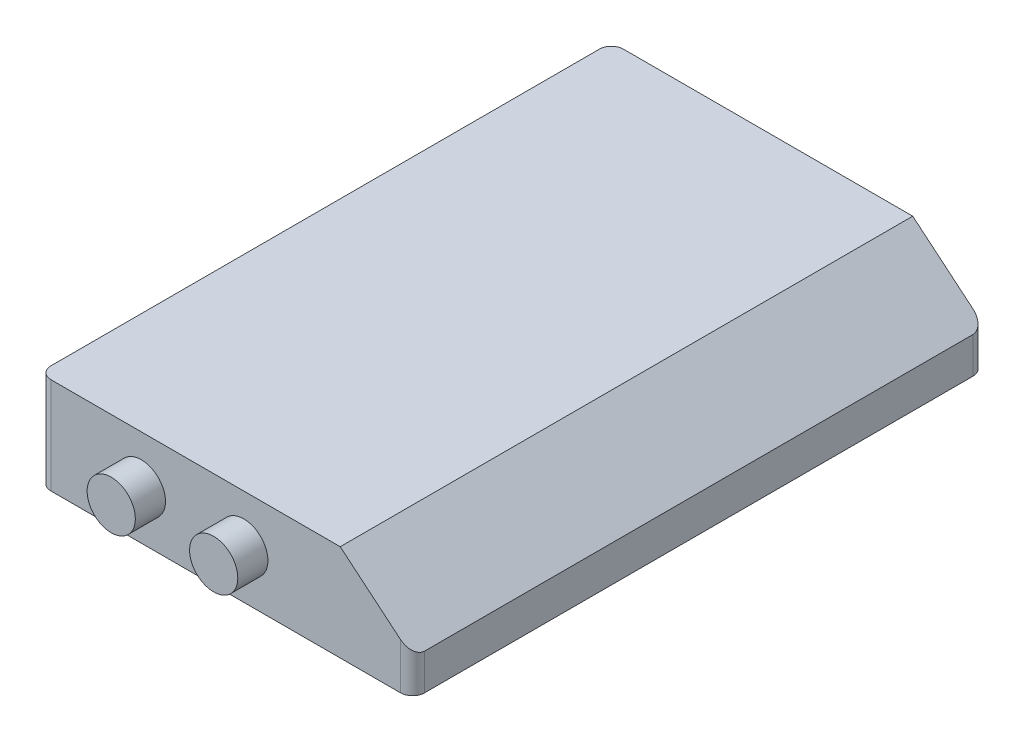
SolidWorks part; units mm, degrees
ref_plane "前视基准面" through (0, 0, 0) normal (0, 0, 1) x (1, 0, 0)
ref_plane "上视基准面" through (0, 0, 0) normal (0, 1, 0) x (1, 0, 0)
ref_plane "右视基准面" through (0, 0, 0) normal (1, 0, 0) x (0, 0, -1)
sketch "草图1" plane through (0, 0, 0) normal (0, 0, 1) x (1, 0, 0)
  line L0 (50, 0) -> (62, 0)
  line L1 (0, 0) -> (50, 0)
  line L2 (0, 0) -> (0, 16)
  line L3 (0, 16) -> (50, 16)
  line L4 (50, 0) -> (50, 16)
  line L5 (62, 0) -> (62, 6)
  line L6 (62, 6) -> (50, 16)
  dimension "D1" = 50
  dimension "D2" = 16
  dimension "D3" = 12
  dimension "D4" = 6
extrude "凸台-拉伸1" add sketch "草图1" against normal blind 95 contours L1 L4 L3 L2 | L5 L6 L4 L0
fillet "圆角1" radius 2 4 edges at (62, 3, 0) (62, 3, -95) (0, 8, 0) (0, 8, -95)
sketch "草图2" plane through (0, 0, 0) normal (0, 0, 1) x (1, 0, 0)
  line L0 (0, 0) -> (0, 16) construction
  line L1 (2, 0) -> (60, 0) construction
  circle A0 centre (17, 8) radius 4
  circle A1 centre (34, 8) radius 4
  dimension "D1" = 17
  dimension "D2" = 34
  dimension "D3" = 8
  dimension "D4" = 8
extrude "凸台-拉伸2" add sketch "草图2" along normal blind 5
